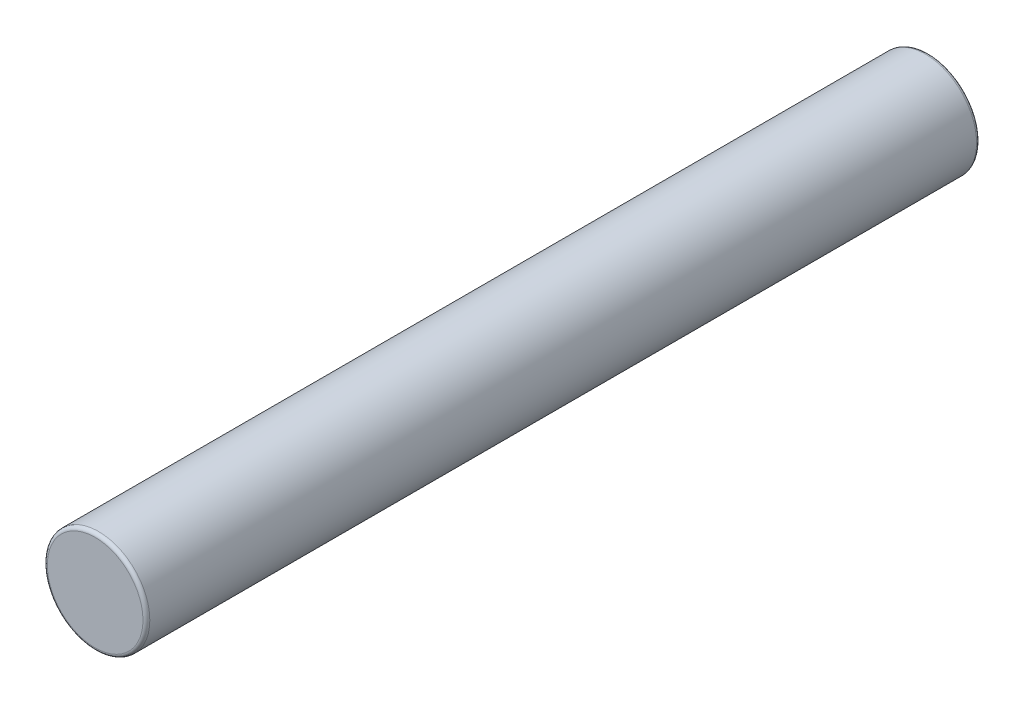
SolidWorks part; units mm, degrees
ref_plane "前基準面" through (0, 0, 0) normal (0, 0, 1) x (1, 0, 0)
ref_plane "上基準面" through (0, 0, 0) normal (0, 1, 0) x (1, 0, 0)
ref_plane "右基準面" through (0, 0, 0) normal (1, 0, 0) x (0, 0, -1)
sketch "草圖1" plane through (0, 0, 0) normal (0, 0, 1) x (1, 0, 0)
  circle A0 centre (0, 0) radius 0.75
  dimension "D1" = 1.5
extrude "伸長1" add sketch "草圖1" along normal blind 12.2
fillet "圓角1" radius 0.05 2 edges at (0.75, 0, 0) (0.75, 0, 12.2)
